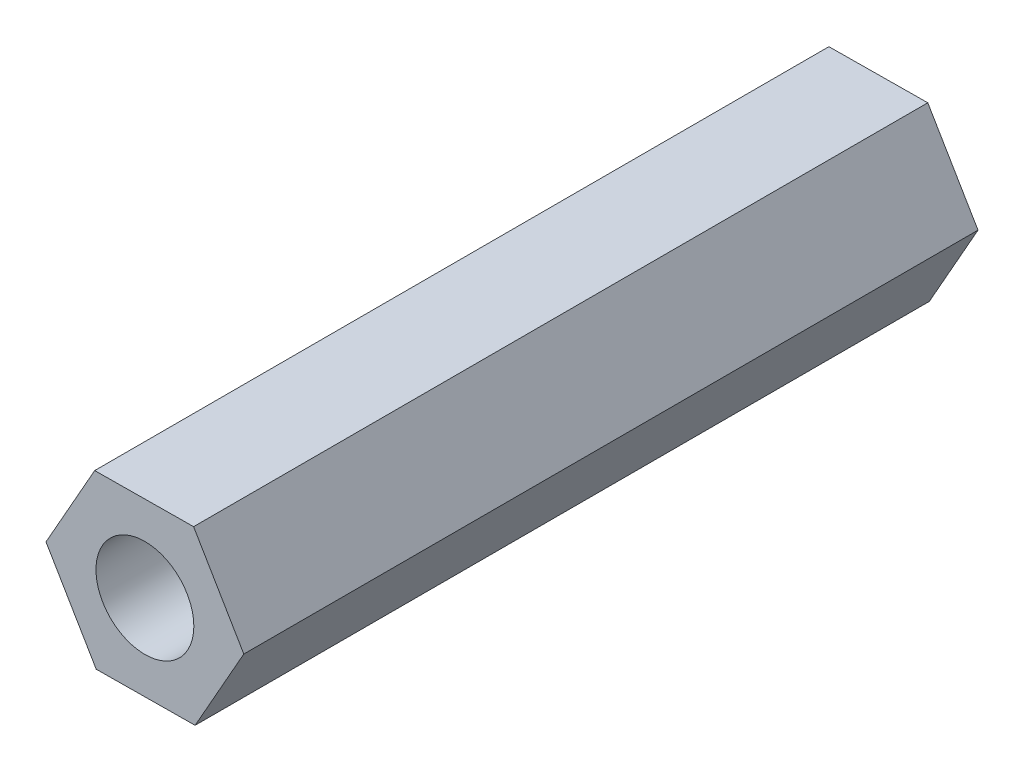
SolidWorks part; units mm, degrees
ref_plane "前视基准面" through (0, 0, 0) normal (0, 0, 1) x (1, 0, 0)
ref_plane "上视基准面" through (0, 0, 0) normal (0, 1, 0) x (1, 0, 0)
ref_plane "右视基准面" through (0, 0, 0) normal (1, 0, 0) x (0, 0, -1)
sketch "草图1" plane through (0, 0, 0) normal (0, 0, 1) x (1, 0, 0)
  line L1 (2.0515, -3.4821) -> (4.0413, 0.0356)
  line L2 (4.0413, 0.0356) -> (1.9898, 3.5177)
  line L3 (1.9898, 3.5177) -> (-2.0515, 3.4821)
  line L4 (-2.0515, 3.4821) -> (-4.0413, -0.0356)
  line L5 (-4.0413, -0.0356) -> (-1.9898, -3.5177)
  line L6 (-1.9898, -3.5177) -> (2.0515, -3.4821)
  circle A0 centre (0, 0) radius 3.5 construction
  circle A1 centre (0, 0) radius 2
extrude "凸台-拉伸1" add sketch "草图1" along normal blind 30
